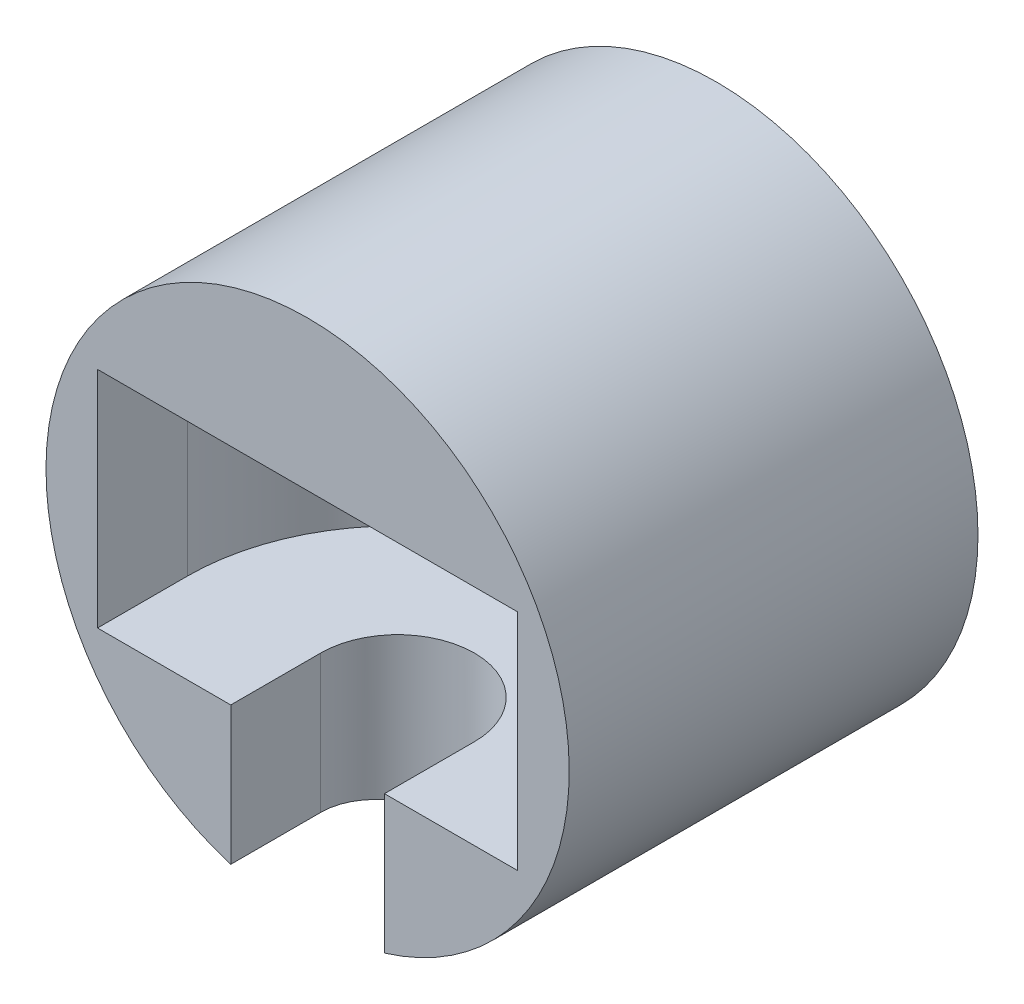
SolidWorks part; units mm, degrees
ref_plane "Front Plane" through (0, 0, 0) normal (0, 0, 1) x (1, 0, 0)
ref_plane "Top Plane" through (0, 0, 0) normal (0, 1, 0) x (1, 0, 0)
ref_plane "Right Plane" through (0, 0, 0) normal (1, 0, 0) x (0, 0, -1)
sketch "Sketch1" plane through (0, 0, 0) normal (0, 0, 1) x (1, 0, 0)
  circle A0 centre (0, 0) radius 16
  circle A1 centre (0, 0) radius 3
extrude "Boss-Extrude1" add sketch "Sketch1" along normal blind 25
sketch "Sketch2" plane through (0, 0, 0) normal (0, 1, 0) x (1, 0, 0)
  line L4 (-12.85, -25) -> (-12.85, -19.5)
  line L5 (-12.85, -25) -> (12.85, -25)
  line L9 (12.85, -25) -> (12.85, -19.5)
  arc A2 (12.85, -19.5) -> (-12.85, -19.5) centre (0, -19.5) ccw
extrude "Cut-Extrude1" cut sketch "Sketch2" against normal mid plane 13.7
sketch "Sketch3" plane through (0, 0, 0) normal (0, 1, 0) x (1, 0, 0)
  line L5 (-4.7, -19.5) -> (-4.7, -25)
  line L6 (-4.7, -25) -> (4.7, -25)
  line L7 (4.7, -19.5) -> (4.7, -25)
  arc A1 (4.7, -19.5) -> (-4.7, -19.5) centre (0, -19.5) ccw
extrude "Cut-Extrude2" cut sketch "Sketch3" against normal up to surface (15.2941 mm away)
